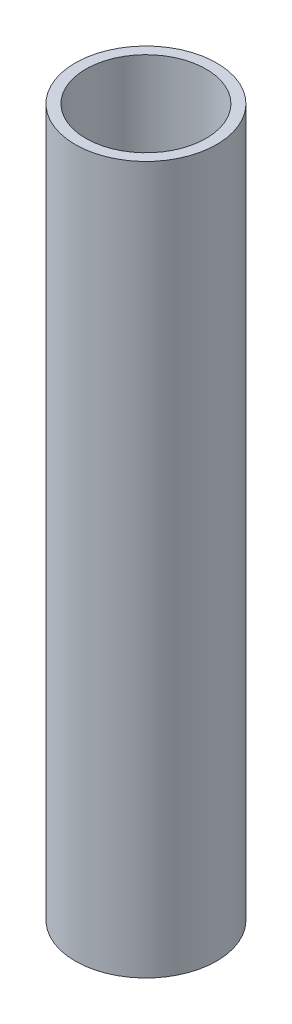
SolidWorks part; units mm, degrees
ref_plane "Front Plane" through (0, 0, 0) normal (0, 0, 1) x (1, 0, 0)
ref_plane "Top Plane" through (0, 0, 0) normal (0, 1, 0) x (1, 0, 0)
ref_plane "Right Plane" through (0, 0, 0) normal (1, 0, 0) x (0, 0, -1)
sketch "cirkel1" plane through (0, 0, 0) normal (0, 1, 0) x (1, 0, 0)
  circle A0 centre (0, 0) radius 10
  dimension "D1" = 20
extrude "cilinder" add sketch "cirkel1" along normal blind 100
sketch "cirkel2" plane through (0, 100, 0) normal (0, 1, 0) x (1, 0, 0)
  circle A0 centre (0, 0) radius 8.5
  dimension "D1" = 17
extrude "cilinder_hol" cut sketch "cirkel2" against normal blind 200
